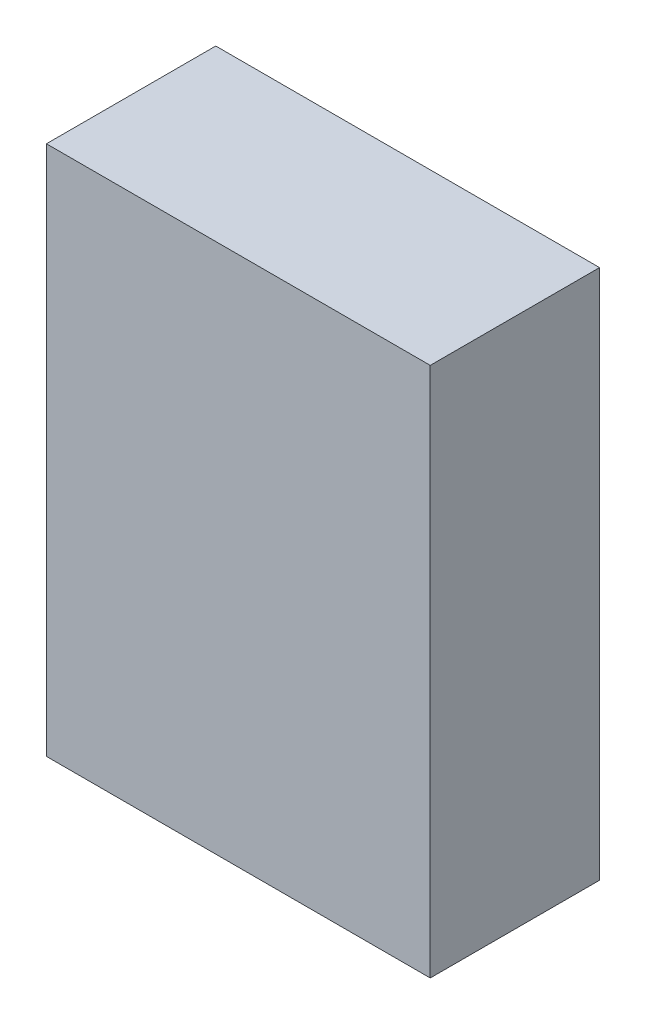
SolidWorks part; units mm, degrees
ref_plane "Front Plane" through (0, 0, 0) normal (0, 0, 1) x (1, 0, 0)
ref_plane "Top Plane" through (0, 0, 0) normal (0, 1, 0) x (1, 0, 0)
ref_plane "Right Plane" through (0, 0, 0) normal (1, 0, 0) x (0, 0, -1)
sketch "Sketch1" plane through (0, 0, 0) normal (0, 1, 0) x (1, 0, 0)
  line L1 (0, 0) -> (34, 0)
  line L2 (0, 0) -> (0, -15)
  line L3 (0, -15) -> (34, -15)
  line L4 (34, 0) -> (34, -15)
  dimension "D1" = 34
  dimension "D2" = 15
extrude "Boss-Extrude1" add sketch "Sketch1" along normal blind 47
